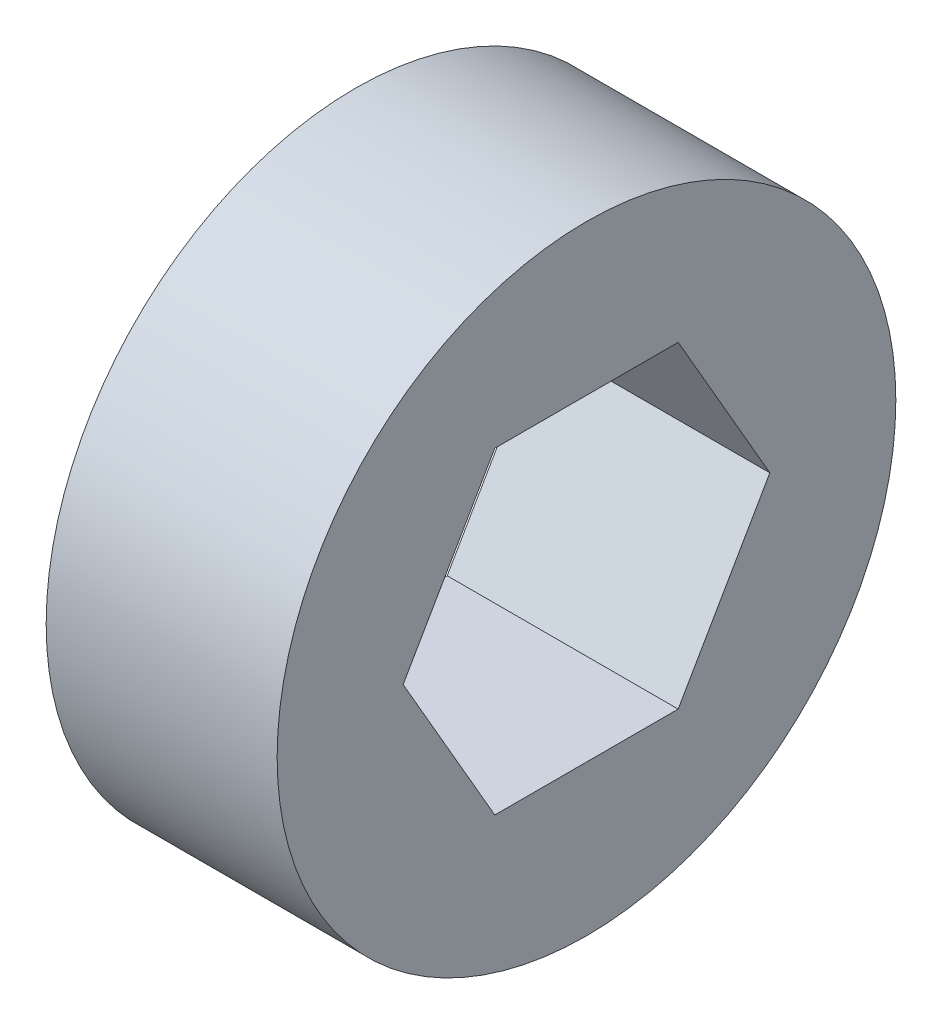
SolidWorks part; units mm, degrees
material "PET"
ref_plane "Front" through (0, 0, 0) normal (0, 0, 1) x (1, 0, 0)
ref_plane "Top" through (0, 0, 0) normal (0, 1, 0) x (1, 0, 0)
ref_plane "Right" through (0, 0, 0) normal (1, 0, 0) x (0, 0, -1)
sketch "Sketch1" plane through (0, 0, 0) normal (1, 0, 0) x (0, 0, -1)
  line L1 (5.6459, 0) -> (2.823, 4.8895)
  line L2 (2.823, 4.8895) -> (-2.823, 4.8895)
  line L3 (-2.823, 4.8895) -> (-5.6459, 0)
  line L4 (-5.6459, 0) -> (-2.823, -4.8895)
  line L5 (-2.823, -4.8895) -> (2.823, -4.8895)
  line L6 (2.823, -4.8895) -> (5.6459, 0)
  circle A0 centre (0, 0) radius 9.525
  circle A1 centre (0, 0) radius 4.8895 construction
  dimension "D2" = 19.05
  dimension "D1" = 9.779
extrude "Boss-Extrude1" add sketch "Sketch1" along normal blind 7.112
